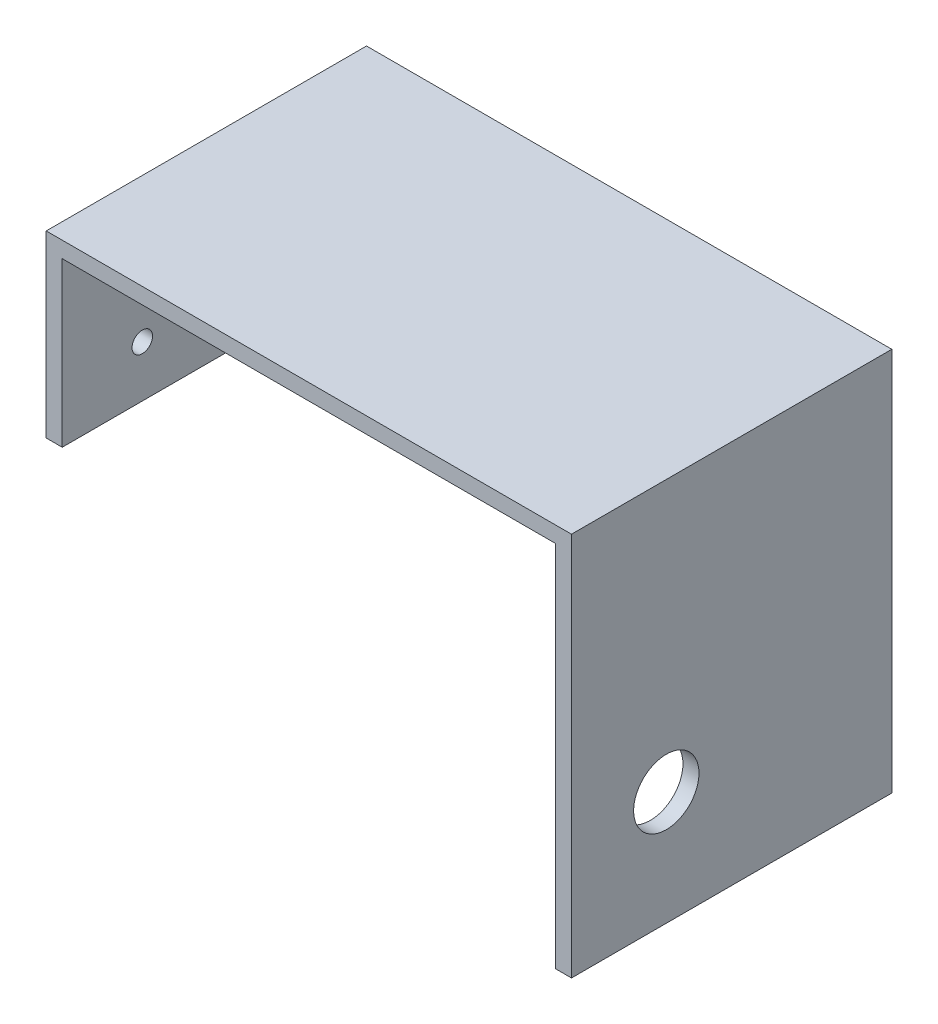
SolidWorks part; units mm, degrees
ref_plane "Front Plane" through (0, 0, 0) normal (0, 0, 1) x (1, 0, 0)
ref_plane "Top Plane" through (0, 0, 0) normal (0, 1, 0) x (1, 0, 0)
ref_plane "Right Plane" through (0, 0, 0) normal (1, 0, 0) x (0, 0, -1)
sketch "Sketch2" plane through (0, 0, 0) normal (0, 0, 1) x (1, 0, 0)
  line L0 (0, 0) -> (-82, 0)
  line L1 (-82, 0) -> (-82, -28)
  line L2 (-82, -28) -> (-79.5, -28)
  line L3 (-79.5, -28) -> (-79.5, -2.5)
  line L4 (-79.5, -2.5) -> (-2.5, -2.5)
  line L5 (-2.5, -2.5) -> (-2.5, -60)
  line L6 (-2.5, -60) -> (0, -60)
  line L7 (0, -60) -> (0, 0)
  dimension "D1" = 2.5
  dimension "D2" = 2.5
  dimension "D3" = 2.5
  dimension "D4" = 82
  dimension "D5" = 28
  dimension "D6" = 60
extrude "Boss-Extrude1" add sketch "Sketch2" along normal blind 50
sketch "Sketch3" plane through (-82, 0, 0) normal (-1, 0, 0) x (0, 0, 1)
  line L0 (0, 0) -> (0, -28) construction
  line L1 (50, 0) -> (50, -28) construction
  line L3 (50, 0) -> (0, 0) construction
  circle A0 centre (12.5, -20) radius 1.6
  circle A1 centre (37.5, -20) radius 1.6
  dimension "D1" = 3.2
  dimension "D2" = 3.2
  dimension "D3" = 25
  dimension "D4" = 12.5
  dimension "D5" = 12.5
  dimension "D7" = 20
extrude "Cut-Extrude1" cut sketch "Sketch3" against normal blind 50
sketch "Sketch4" plane through (0, 0, 0) normal (1, 0, 0) x (0, 0, -1)
  line L0 (-50, -60) -> (-50, 0) construction
  line L3 (-50, -60) -> (0, -60) construction
  circle A0 centre (-35.2, -42.25) radius 5.1
  dimension "D1" = 10.2
  dimension "D2" = 14.8
  dimension "D3" = 17.75
extrude "Cut-Extrude2" cut sketch "Sketch4" against normal blind 50
